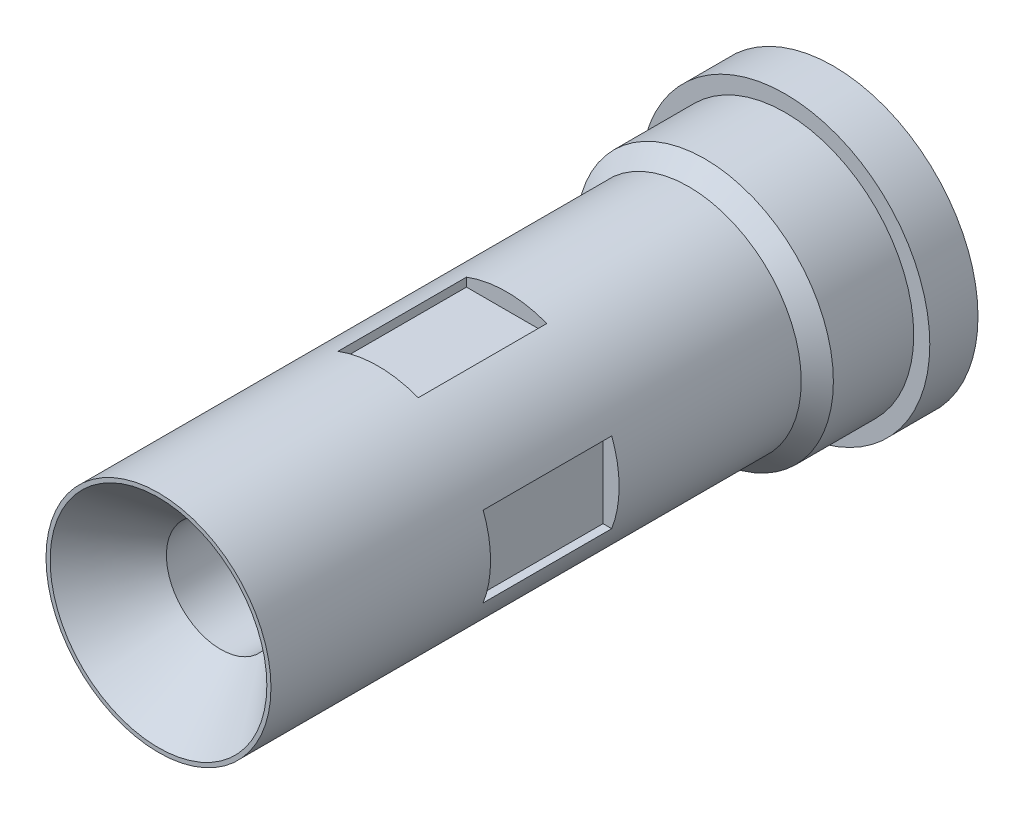
SolidWorks part; units mm, degrees
material "PE High Density"
ref_plane "Front" through (0, 0, 0) normal (0, 0, 1) x (1, 0, 0)
ref_plane "Top" through (0, 0, 0) normal (0, 1, 0) x (1, 0, 0)
ref_plane "Right" through (0, 0, 0) normal (1, 0, 0) x (0, 0, -1)
sketch "Sketch1" plane through (0, 0, 0) normal (0, 0, 1) x (1, 0, 0)
  circle A0 centre (0, 0) radius 9
extrude "Boss-Extrude1" add sketch "Sketch1" along normal blind 4 contours A0
sketch "Sketch2" plane through (0, 0, 4) normal (0, 0, 1) x (1, 0, 0)
  circle A0 centre (0, 0) radius 7
extrude "Boss-Extrude2" add sketch "Sketch2" along normal blind 39
hole_wizard "CSK for 1/4 Flat Head Socket Cap Screw1" positions "Sketch3" profile "Sketch4" countersink size "1/4" standard "ANSI Inch" end condition up to next
sketch "Sketch3" plane through (0, 0, 43) normal (0, 0, 1) x (1, 0, 0)
  point P0 (0, 0)
sketch "Sketch4" plane through (0, 0, 43) normal (1, 0, 0) x (0, -1, 0)
  line L0 (0, 0) -> (0, 43)
  line L1 (0, 43) -> (3.3782, 43)
  line L2 (3.3782, 43) -> (3.3782, 3.8716)
  line L3 (3.3782, 3.8716) -> (6.7437, 0)
  line L5 (6.7437, 0) -> (0, 0)
  line L6 (-3.3782, 3.8716) -> (-6.7437, 0) construction
  line L11 (0, -6.35) -> (0, 107.95) construction
  dimension "Thru Hole Dia." = 6.7564
  dimension "Thru Hole Depth" = 43
  dimension "Near C'Sink Dia." = 13.4874
  dimension "Near C'Sink Angle" = 82
ref_plane "Plane1" through (0, 0, 11) normal (0, 0, 1) x (1, 0, 0)
sketch "Sketch6" plane through (0, 0, 0) normal (0, 0, -1) x (-1, 0, 0)
  circle A0 centre (0, 0) radius 16
extrude "Cut-Extrude1" cut sketch "Sketch6" against normal blind 1 contours A0
sketch "Sketch7" plane through (0, 0, 1) normal (0, 0, -1) x (-1, 0, 0)
  circle A0 centre (0, 0) radius 4
extrude "Cut-Extrude2" cut sketch "Sketch7" against normal blind 3 contours A0
ref_plane "Plane2" through (6, 0, 0) normal (1, 0, 0) x (0, 0, -1)
sketch "Sketch9" plane through (6, 0, 0) normal (1, 0, 0) x (0, 0, -1)
  line L1 (-29.3337, -2.5) -> (-21.3337, -2.5)
  line L2 (-29.3337, -2.5) -> (-29.3337, 2.5)
  line L3 (-29.3337, 2.5) -> (-21.3337, 2.5)
  line L4 (-21.3337, -2.5) -> (-21.3337, 2.5)
  line L5 (-29.3337, -2.5) -> (-21.3337, 2.5) construction
  line L6 (-29.3337, 2.5) -> (-21.3337, -2.5) construction
  point P0 (-25.3337, 0)
extrude "Cut-Extrude3" cut sketch "Sketch9" along normal blind 3
pattern_circular "CirPattern1" count 4 every 90 about axis through (0, 0, 0) along (0, 0, 1) of "Cut-Extrude3"
sketch "Sketch10" plane through (0, 0, 4) normal (0, 0, 1) x (1, 0, 0)
  circle A0 centre (0, 0) radius 8
extrude "Boss-Extrude3" add sketch "Sketch10" along normal blind 5
ref_plane "Plane3" through (0, 0, 10) normal (0, 0, 1) x (1, 0, 0)
sketch "Sketch11" plane through (0, 0, 10) normal (0, 0, 1) x (1, 0, 0)
  circle A0 centre (0, 0) radius 7
loft "Loft4" add profiles "Sketch11" section edge at (8, 0, 9) section "Sketch11"
sketch "Sketch12" plane through (0, 0, 10) normal (0, 0, 1) x (1, 0, 0)
  circle A0 centre (0, 0) radius 3.3782
extrude "Cut-Extrude4" cut sketch "Sketch12" against normal blind 9
